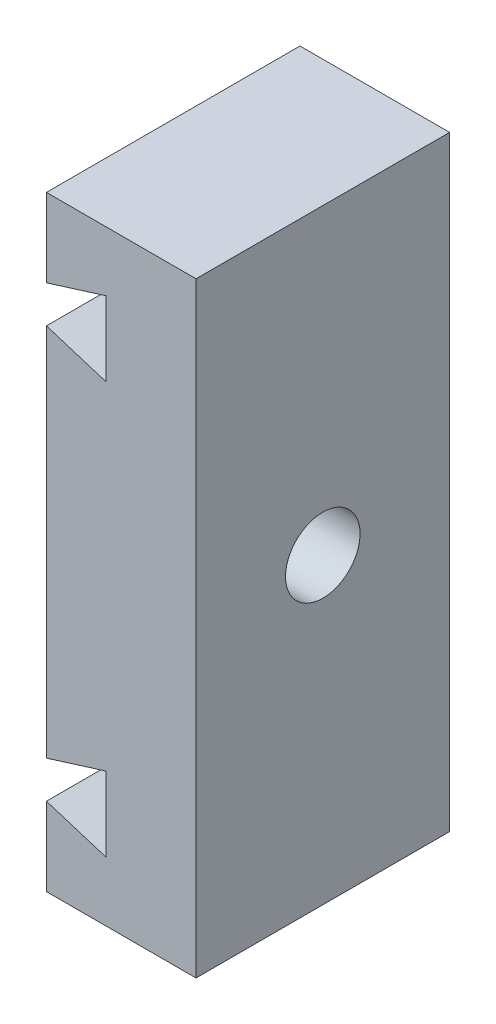
SolidWorks part; units mm, degrees
ref_plane "Alzado" through (0, 0, 0) normal (0, 0, 1) x (1, 0, 0)
ref_plane "Planta" through (0, 0, 0) normal (0, 1, 0) x (1, 0, 0)
ref_plane "Vista lateral" through (0, 0, 0) normal (1, 0, 0) x (0, 0, -1)
sketch "Croquis1" plane through (0, 0, 0) normal (0, 0, 1) x (1, 0, 0)
  line L5 (12.15, 8.15) -> (12.15, 5.65)
  line L16 (10.15, 10.15) -> (10.15, 7.525)
  line L17 (10.15, 10.15) -> (15.1656, 10.15)
  line L18 (15.1656, 10.15) -> (15.1656, -10.15)
  line L19 (12.15, 5.65) -> (10.15, 6.275)
  line L20 (12.15, 8.15) -> (10.15, 7.525)
  line L21 (12.15, -5.65) -> (10.15, -6.275)
  line L22 (12.15, -5.65) -> (12.15, -8.15)
  line L23 (12.15, -8.15) -> (10.15, -7.525)
  line L24 (10.15, 6.275) -> (10.15, -6.275)
  line L25 (10.15, -7.525) -> (10.15, -10.15)
  line L26 (15.1656, -10.15) -> (10.15, -10.15)
  point P12 (12.15, 6.9)
  dimension "D4" = 2.5
  dimension "D5" = 1.25
  dimension "D6" = 0.625
  dimension "D7" = 2
  dimension "D8" = 2
  dimension "D9" = 2
extrude "Saliente-Extruir1" add sketch "Croquis1" along normal blind 8.5
sketch "Croquis2" plane through (10.15, 0, 0) normal (-1, 0, 0) x (0, 0, 1)
  line L0 (8.5, 6.275) -> (0, 6.275) construction
  circle A0 centre (4.25, 0) radius 1.25
  point P2 (0, 0)
  point P5 (4.25, 6.275)
  dimension "D1" = 2.5
extrude "Cortar-Extruir1" cut sketch "Croquis2" against normal blind 8.5
sketch "Croquis3" plane through (10.15, 0, 0) normal (-1, 0, 0) x (0, 0, 1)
  circle A0 centre (4.25, 0) radius 3
  dimension "D1" = 6
extrude "Cortar-Extruir2" cut sketch "Croquis3" against normal blind 2.5
